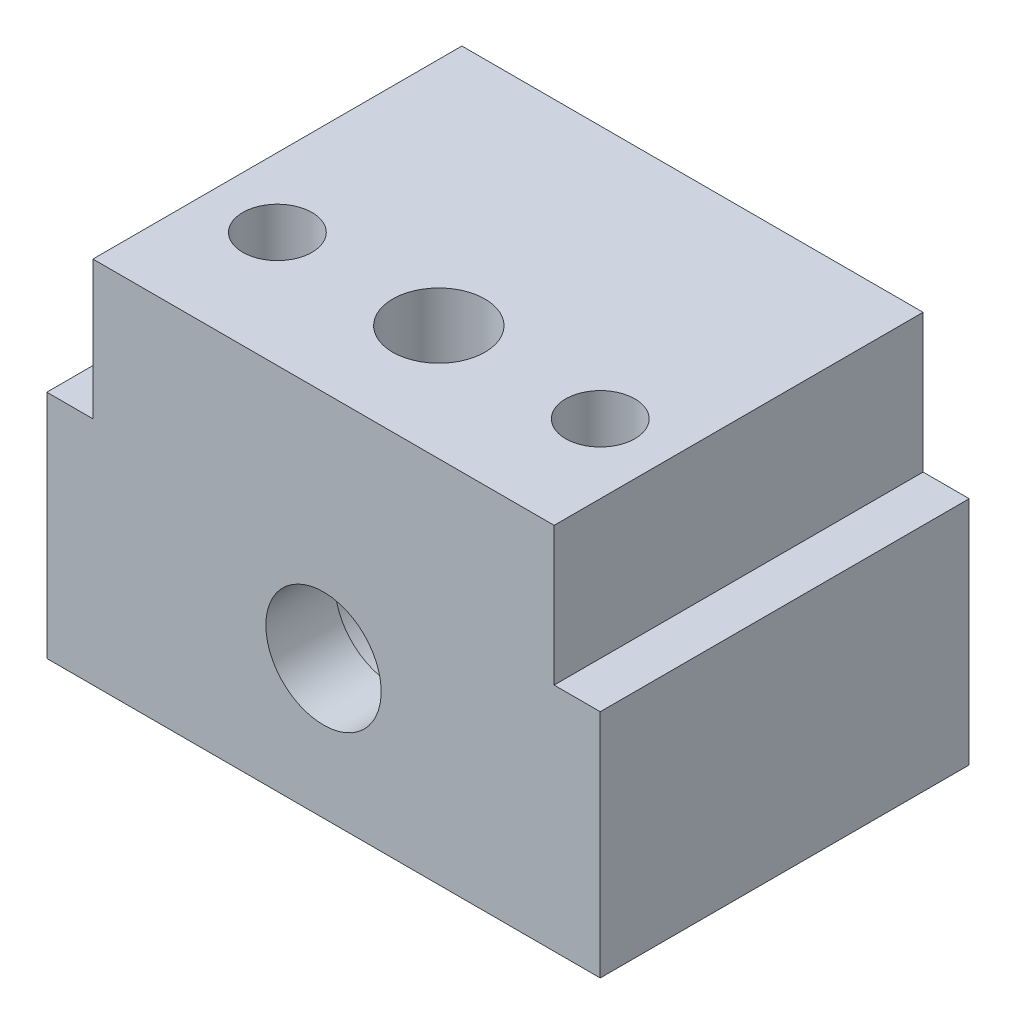
SolidWorks part; units mm, degrees
material "PVC 0.007 Plasticized"
ref_plane "Front Plane" through (0, 0, 0) normal (0, 0, 1) x (1, 0, 0)
ref_plane "Top Plane" through (0, 0, 0) normal (0, 1, 0) x (1, 0, 0)
ref_plane "Right Plane" through (0, 0, 0) normal (1, 0, 0) x (0, 0, -1)
other "Configuration Table"
sketch "Sketch1" plane through (0, 0, 0) normal (0, 0, 1) x (1, 0, 0)
  line L0 (0, 0) -> (0, 12.7)
  line L1 (0, 12.7) -> (2.54, 12.7)
  line L2 (2.54, 12.7) -> (2.54, 20.32)
  line L3 (2.54, 20.32) -> (27.94, 20.32)
  line L4 (27.94, 20.32) -> (27.94, 12.7)
  line L5 (27.94, 12.7) -> (30.48, 12.7)
  line L6 (30.48, 12.7) -> (30.48, 0)
  line L7 (30.48, 0) -> (0, 0)
  dimension "D1" = 30.48
  dimension "D2" = 25.4
  dimension "D3" = 12.7
  dimension "D4" = 12.7
  dimension "D5" = 20.32
extrude "Boss-Extrude1" add sketch "Sketch1" against normal blind 20.32
hole_wizard "CBORE for #0 Binding Head Machine Screw1" positions "Sketch3" profile "Sketch4" counterbore size "#0" standard "ANSI Inch" end condition through all
sketch "Sketch3" plane through (0, 0, -20.32) normal (0, 0, -1) x (-1, 0, 0)
  point P0 (-15.24, 7.62)
  dimension "D1" = 7.62
  dimension "D2" = 12.7
sketch "Sketch4" plane through (15.24, 7.62, -20.32) normal (1, 0, 0) x (0, 1, 0)
  line L0 (0, 0) -> (0, 20.32)
  line L1 (0, 20.32) -> (3.175, 20.32)
  line L3 (3.175, 20.32) -> (3.175, 16.51)
  line L4 (3.175, 16.51) -> (4.445, 16.51)
  line L5 (4.445, 16.51) -> (4.445, 0)
  line L7 (4.445, 0) -> (0, 0)
  line L11 (0, -6.35) -> (0, 107.95) construction
  dimension "Thru Hole Dia." = 6.35
  dimension "Thru Hole Depth" = 20.32
  dimension "C'Bore Dia." = 8.89
  dimension "C'Bore Depth" = 16.51
sketch "Sketch5" plane through (0, 20.32, 0) normal (0, 1, 0) x (1, 0, 0)
  line L1 (0, 20.32) -> (0, 0) construction
  line L2 (30.48, 20.32) -> (30.48, 0) construction
  line L3 (27.94, 0) -> (2.54, 0) construction
  circle A0 centre (6.35, 6.35) radius 1.905
  circle A1 centre (15.24, 6.35) radius 2.54
  circle A2 centre (24.13, 6.35) radius 1.905
  dimension "D1" = 3.81
  dimension "D2" = 3.81
  dimension "D3" = 5.08
  dimension "D6" = 15.24
  dimension "D4" = 6.35
  dimension "D5" = 6.35
  dimension "D7" = 6.35
extrude "Cut-Extrude1" cut sketch "Sketch5" against normal through all and the other way through all contours A0 | A2
sketch "Sketch6" plane through (0, 20.32, 0) normal (0, 1, 0) x (1, 0, 0)
  line L0 (0, 20.32) -> (0, 0) construction
  circle A0 centre (15.24, 6.35) radius 2.54
  dimension "D1" = 5.08
  dimension "D2" = 15.24
extrude "Cut-Extrude2" cut sketch "Sketch6" against normal blind 7.62
sketch "Sketch7" plane through (0, 0, 0) normal (0, -1, 0) x (1, 0, 0)
  line L1 (1.9506, -6.35) -> (4.1503, -10.16)
  line L2 (4.1503, -10.16) -> (8.5497, -10.16)
  line L3 (8.5497, -10.16) -> (10.7494, -6.35)
  line L4 (10.7494, -6.35) -> (8.5497, -2.54)
  line L5 (8.5497, -2.54) -> (4.1503, -2.54)
  line L6 (4.1503, -2.54) -> (1.9506, -6.35)
  line L13 (19.7306, -6.35) -> (21.9303, -10.16)
  line L14 (21.9303, -10.16) -> (26.3297, -10.16)
  line L15 (26.3297, -10.16) -> (28.5294, -6.35)
  line L16 (28.5294, -6.35) -> (26.3297, -2.54)
  line L17 (26.3297, -2.54) -> (21.9303, -2.54)
  line L18 (21.9303, -2.54) -> (19.7306, -6.35)
  circle A0 centre (6.35, -6.35) radius 3.81 construction
  circle A2 centre (24.13, -6.35) radius 3.81 construction
  dimension "D1" = 7.62
  dimension "D2" = 7.62
extrude "Cut-Extrude3" cut sketch "Sketch7" against normal blind 7.62
